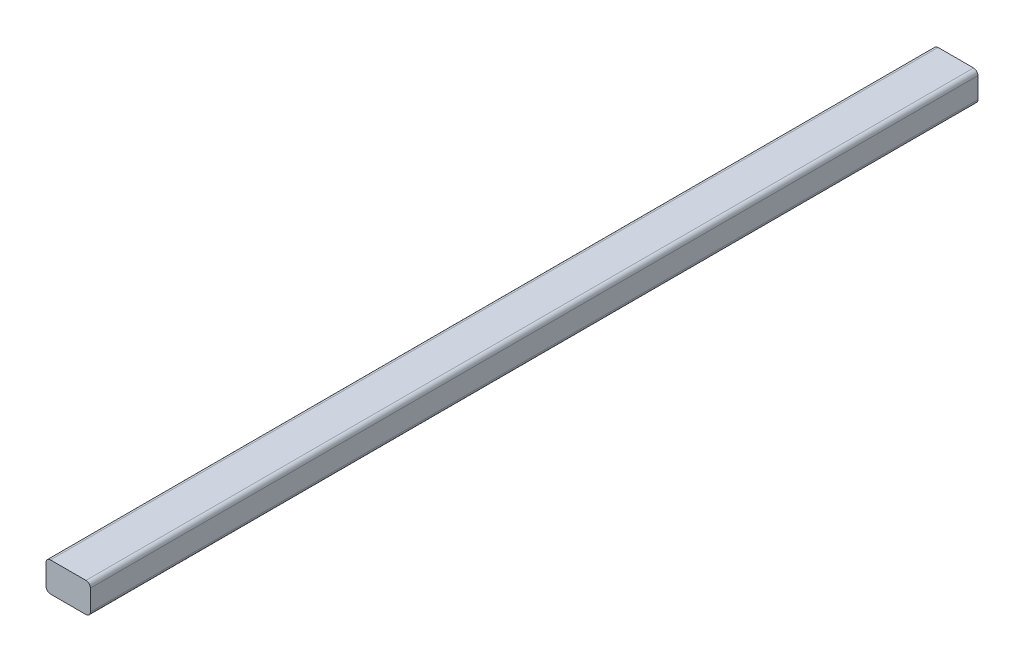
SolidWorks part; units mm, degrees
ref_plane "Front" through (0, 0, 0) normal (0, 0, 1) x (1, 0, 0)
ref_plane "Top" through (0, 0, 0) normal (0, 1, 0) x (1, 0, 0)
ref_plane "Right" through (0, 0, 0) normal (1, 0, 0) x (0, 0, -1)
sketch "Esquisse1" plane through (0, 0, 0) normal (0, 0, 1) x (1, 0, 0)
  line L1 (0, 0) -> (30, 0)
  line L2 (0, 0) -> (0, 20)
  line L3 (0, 20) -> (30, 20)
  line L4 (30, 0) -> (30, 20)
  dimension "D1" = 30
  dimension "D2" = 20
extrude "Boss.-Extru.1" add sketch "Esquisse1" along normal blind 600
fillet "Congé1" radius 3 4 edges at (30, 0, 300) (0, 0, 300) (0, 20, 300) (30, 20, 300)
